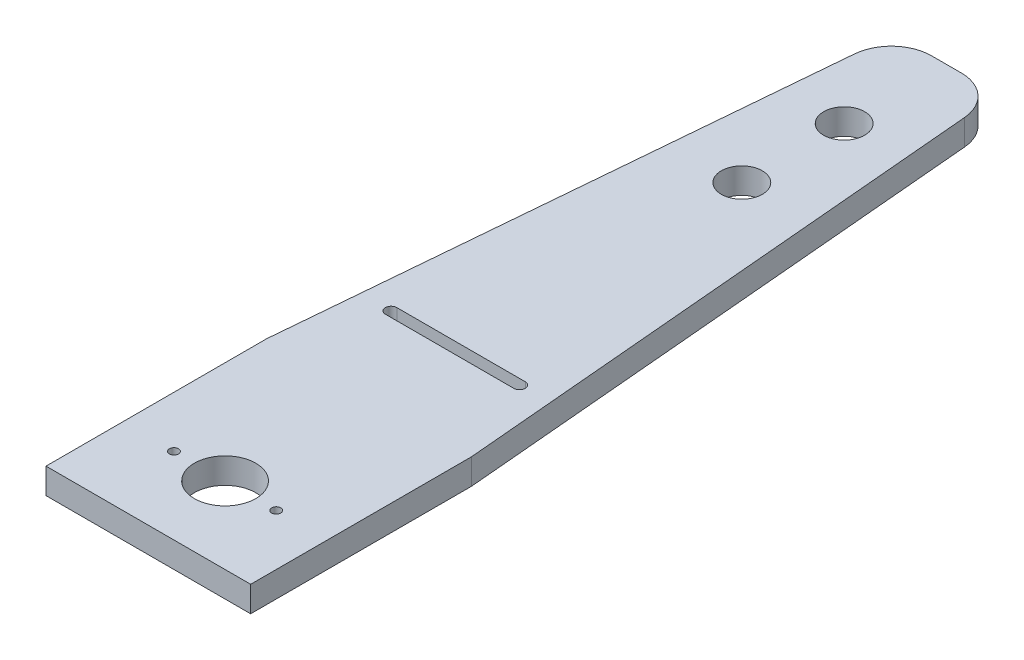
SolidWorks part; units mm, degrees
material "Acrylic (Medium-high impact)"
ref_plane "Front Plane" through (0, 0, 0) normal (0, 0, 1) x (1, 0, 0)
ref_plane "Top Plane" through (0, 0, 0) normal (0, 1, 0) x (1, 0, 0)
ref_plane "Right Plane" through (0, 0, 0) normal (1, 0, 0) x (0, 0, -1)
sketch "Sketch1" plane through (0, 0, 0) normal (0, 1, 0) x (1, 0, 0)
  line L1 (0, 0) -> (50.8, 0)
  line L2 (0, 0) -> (0, 198.12)
  line L3 (0, 198.12) -> (50.8, 198.12)
  line L4 (50.8, 0) -> (50.8, 198.12)
  circle A0 centre (12.7, 19.05) radius 1.1303
  circle A1 centre (38.1, 19.05) radius 1.1303
  circle A2 centre (25.4, 19.05) radius 7.62
  point P11 (25.4, 0)
  dimension "D3" = 2.2606
  dimension "D7" = 15.24
  dimension "D1" = 50.8
  dimension "D2" = 198.12
  dimension "D4" = 19.05
  dimension "D5" = 12.7
  dimension "D6" = 25.4
extrude "Boss-Extrude1" add sketch "Sketch1" along normal blind 6.35
sketch "Sketch2" plane through (0, 6.35, 0) normal (0, 1, 0) x (1, 0, 0)
  line L0 (50.8, 198.12) -> (0, 198.12) construction
  circle A0 centre (25.4, 172.72) radius 5.08
  circle A1 centre (25.4, 147.32) radius 5.08
  point P5 (25.4, 198.12)
  dimension "D1" = 10.16
  dimension "D2" = 25.4
  dimension "D3" = 25.4
extrude "Cut-Extrude1" cut sketch "Sketch2" against normal blind 6.35
chamfer "Chamfer1" distance 12.54 angle 85 2 edges at (50.8, 3.175, -198.12) (0, 3.175, -198.12)
fillet "Fillet1" radius 10 2 edges at (12.54, 3.175, -198.12) (38.26, 3.175, -198.12)
sketch "Sketch3" plane through (0, 6.35, 0) normal (0, 1, 0) x (1, 0, 0)
  line L1 (9.4594, 77.6224) -> (41.3406, 77.6224)
  line L2 (9.4594, 74.7776) -> (41.3406, 74.7776)
  line L3 (0, 0) -> (50.8, 0) construction
  arc A0 (9.4594, 77.6224) -> (9.4594, 74.7776) centre (9.4594, 76.2) ccw
  arc A1 (41.3406, 74.7776) -> (41.3406, 77.6224) centre (41.3406, 76.2) ccw
  point P11 (42.763, 76.2)
  point P13 (25.4, 0)
  point P16 (25.4, 74.7776)
  dimension "D1" = 2.8448
  dimension "D2" = 76.2
extrude "Cut-Extrude2" cut sketch "Sketch3" against normal blind 10.668
